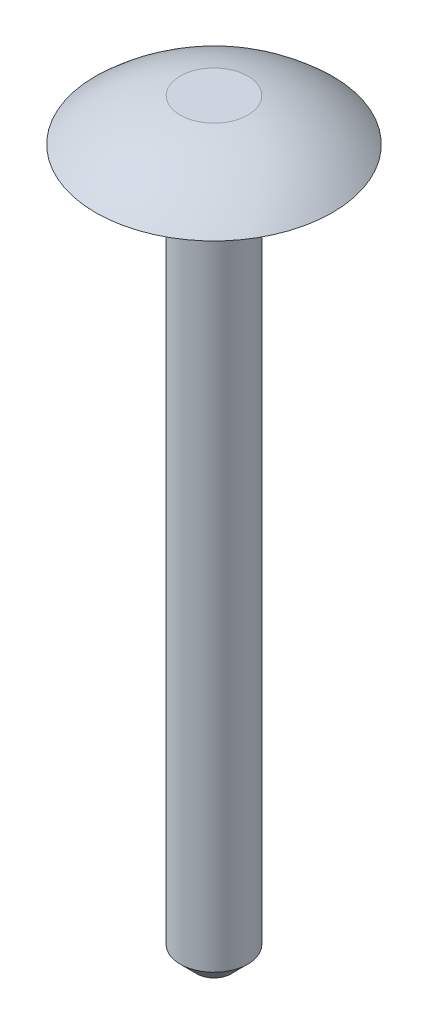
SolidWorks part; units mm, degrees
material "延性铁 (SN)"
ref_plane "前视基准面" through (0, 0, 0) normal (0, 0, 1) x (1, 0, 0)
ref_plane "上视基准面" through (0, 0, 0) normal (0, 1, 0) x (1, 0, 0)
ref_plane "右视基准面" through (0, 0, 0) normal (1, 0, 0) x (0, 0, -1)
other "Configuration Table"
sketch "草图16" plane through (0, 0, 0) normal (0, 0, 1) x (1, 0, 0)
  line L0 (0, 0) -> (-7, 0)
  line L1 (0, 0) -> (0, 2.5)
  line L2 (0, 2.5) -> (-2, 2.5)
  spline S0 degree 2 poles (-2, 2.5) (-4.8209, 1.9722) (-7, 0) knots 0 0 0 1 1 1
revolve "旋转1" add sketch "草图16" angle 360 about L1
sketch "草图19" plane through (0, 0, 0) normal (0, 1, 0) x (1, 0, 0)
  circle A0 centre (0, 0) radius 2
  dimension "D1" = 4
extrude "凸台-拉伸1" add sketch "草图19" against normal blind 42
chamfer "倒角1" distance 1 angle 45 2 edges at (0, 0, 2) (0, -42, 2)
